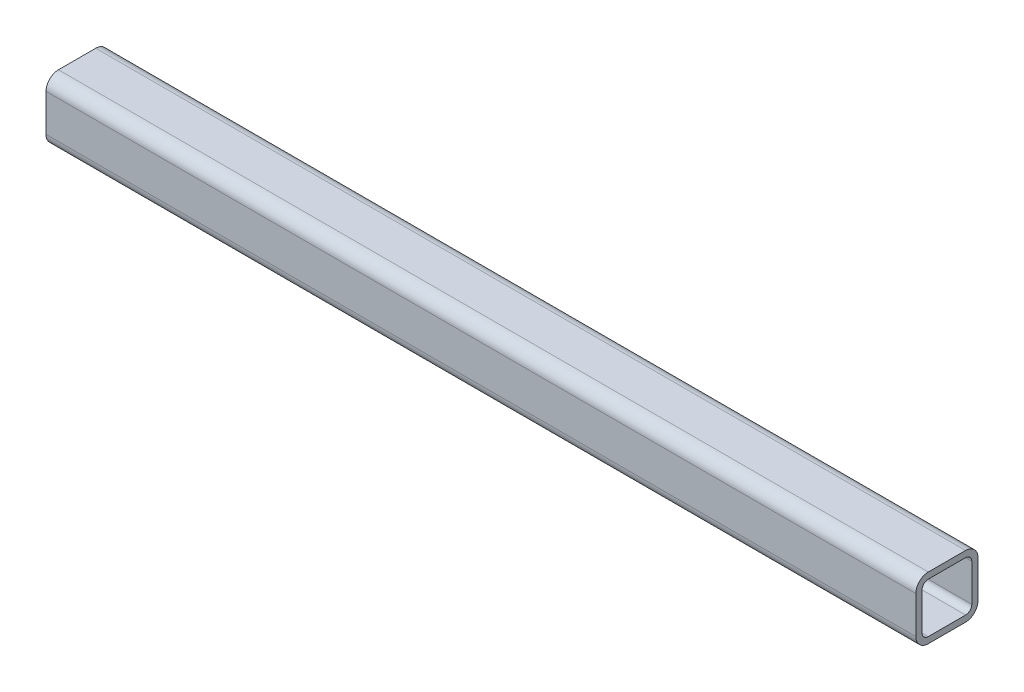
SolidWorks part; units mm, degrees
material "ASTM A36 Acero"
ref_plane "Alzado" through (0, 0, 0) normal (0, 0, 1) x (1, 0, 0)
ref_plane "Planta" through (0, 0, 0) normal (0, 1, 0) x (1, 0, 0)
ref_plane "Vista lateral" through (0, 0, 0) normal (1, 0, 0) x (0, 0, -1)
sketch "Croquis1" plane through (0, 0, 0) normal (0, 0, 1) x (1, 0, 0)
  line L0 (0, 0) -> (700, 0)
  dimension "D1" = 700
other "Tube (square) RHS50X50X5(1)"
ref_plane "Plano1" through (0, 0, 0) normal (1, 0, 0) x (0, 1, 0)
sketch "Sketch1" plane through (0, 0, 0) normal (1, 0, 0) x (0, 1, 0)
  line L0 (-15, -20) -> (15, -20)
  line L1 (-20, -15) -> (-20, 15)
  line L2 (15, 20) -> (-15, 20)
  line L3 (20, 15) -> (20, -15)
  line L4 (-15, -25) -> (15, -25)
  line L5 (-25, -15) -> (-25, 15)
  line L6 (15, 25) -> (-15, 25)
  line L7 (25, 15) -> (25, -15)
  line L8 (-25, 0) -> (-20, 0) construction
  line L9 (-20, 0) -> (20, 0) construction
  line L10 (20, 0) -> (25, 0) construction
  line L11 (0, 25) -> (0, 20) construction
  line L12 (0, 20) -> (0, -20) construction
  line L13 (0, -20) -> (0, -25) construction
  arc A0 (25, 15) -> (15, 25) centre (15, 15) ccw
  arc A1 (15, -25) -> (25, -15) centre (15, -15) ccw
  arc A2 (-25, -15) -> (-15, -25) centre (-15, -15) ccw
  arc A3 (-15, 25) -> (-25, 15) centre (-15, 15) ccw
  arc A4 (-15, 20) -> (-20, 15) centre (-15, 15) ccw
  arc A5 (20, 15) -> (15, 20) centre (15, 15) ccw
  arc A6 (15, -20) -> (20, -15) centre (15, -15) ccw
  arc A7 (-20, -15) -> (-15, -20) centre (-15, -15) ccw
  point P6 (-25, 25)
  point P33 (0, 0)
  point P35 (25, 25)
  point P36 (-25, -25)
  point P37 (25, -25)
  dimension "D1" = 10
  dimension "Thickness" = 5
  dimension "V_leg" = 50
  dimension "H_leg" = 50
